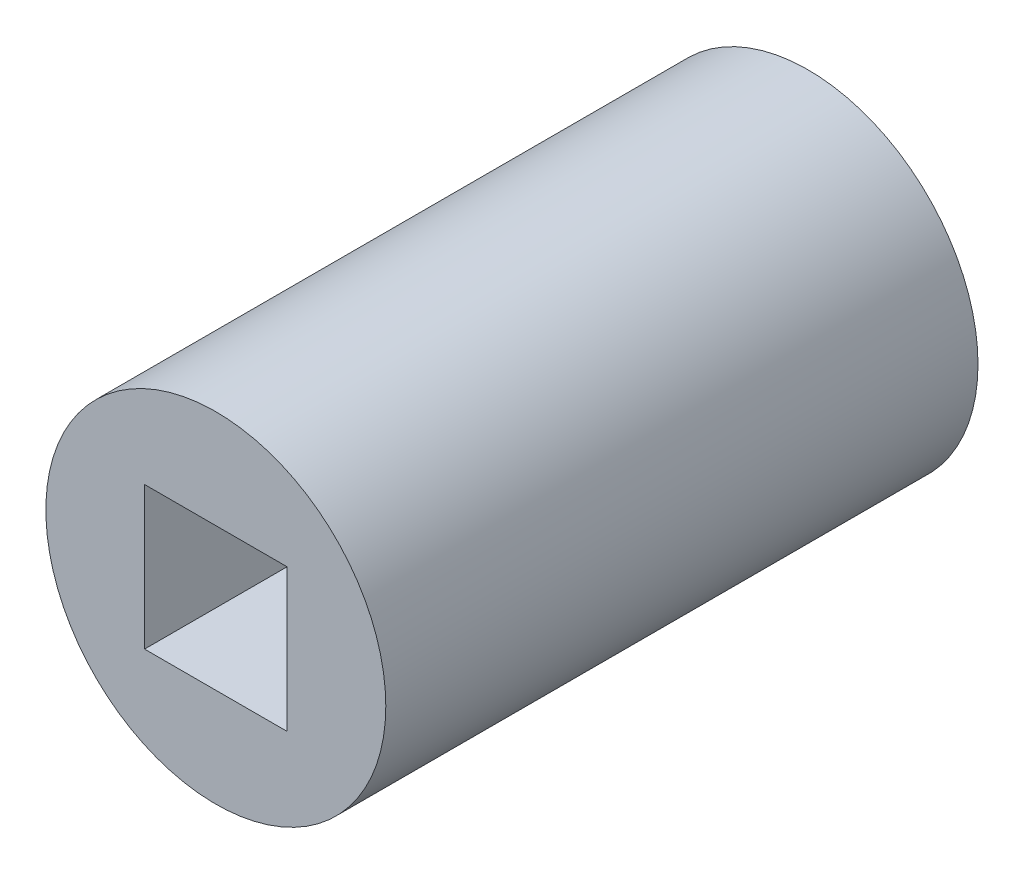
SolidWorks part; units mm, degrees
ref_plane "Alzado" through (0, 0, 0) normal (0, 0, 1) x (1, 0, 0)
ref_plane "Planta" through (0, 0, 0) normal (0, 1, 0) x (1, 0, 0)
ref_plane "Vista lateral" through (0, 0, 0) normal (1, 0, 0) x (0, 0, -1)
sketch "Croquis1" plane through (0, 0, 0) normal (0, 0, 1) x (1, 0, 0)
  circle A0 centre (0, 0) radius 7.75
  dimension "D1" = 15.5
extrude "Saliente-Extruir1" add sketch "Croquis1" against normal blind 27
sketch "Croquis2" plane through (0, 0, 0) normal (0, 0, 1) x (1, 0, 0)
  line L1 (3.25, -3.25) -> (-3.25, -3.25)
  line L2 (3.25, -3.25) -> (3.25, 3.25)
  line L3 (3.25, 3.25) -> (-3.25, 3.25)
  line L4 (-3.25, -3.25) -> (-3.25, 3.25)
  line L5 (3.25, -3.25) -> (-3.25, 3.25) construction
  line L6 (3.25, 3.25) -> (-3.25, -3.25) construction
  point P0 (0, 0)
  dimension "D1" = 6.5
  dimension "D2" = 6.5
extrude "Cortar-Extruir1" cut sketch "Croquis2" against normal through all
sketch "Croquis3" plane through (0, 0, -27) normal (0, 0, -1) x (-1, 0, 0)
  circle A0 centre (0, 0) radius 5
extrude "Saliente-Extruir2" add sketch "Croquis3" against normal blind 5
sketch "Croquis4" plane through (0, 0, -27) normal (0, 0, -1) x (-1, 0, 0)
  circle A0 centre (0, 0) radius 1.75
  dimension "D1" = 3.5
extrude "Cortar-Extruir2" cut sketch "Croquis4" against normal through all
sketch "Croquis5" plane through (0, 0, -27) normal (0, 0, -1) x (-1, 0, 0)
  circle A0 centre (0, 0) radius 3.25
  dimension "D1" = 6.5
extrude "Cortar-Extruir3" cut sketch "Croquis5" against normal blind 10
